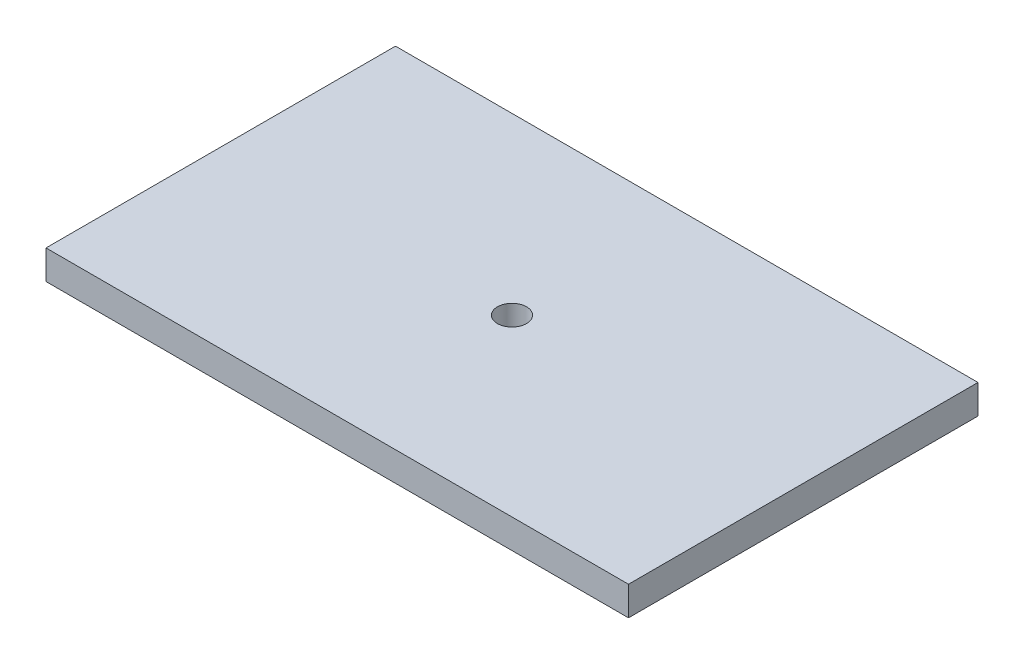
SolidWorks part; units mm, degrees
ref_plane "Front Plane" through (0, 0, 0) normal (0, 0, 1) x (1, 0, 0)
ref_plane "Top Plane" through (0, 0, 0) normal (0, 1, 0) x (1, 0, 0)
ref_plane "Right Plane" through (0, 0, 0) normal (1, 0, 0) x (0, 0, -1)
sketch "Sketch1" plane through (0, 0, 0) normal (0, 1, 0) x (1, 0, 0)
  line L1 (100, 60) -> (-100, 60)
  line L2 (100, 60) -> (100, -60)
  line L3 (100, -60) -> (-100, -60)
  line L4 (-100, 60) -> (-100, -60)
  line L5 (100, 60) -> (-100, -60) construction
  line L6 (100, -60) -> (-100, 60) construction
  circle A0 centre (0, 0) radius 5
  point P0 (0, 0)
  dimension "D3" = 10
  dimension "D1" = 120
  dimension "D2" = 200
extrude "Boss-Extrude1" add sketch "Sketch1" along normal blind 10
